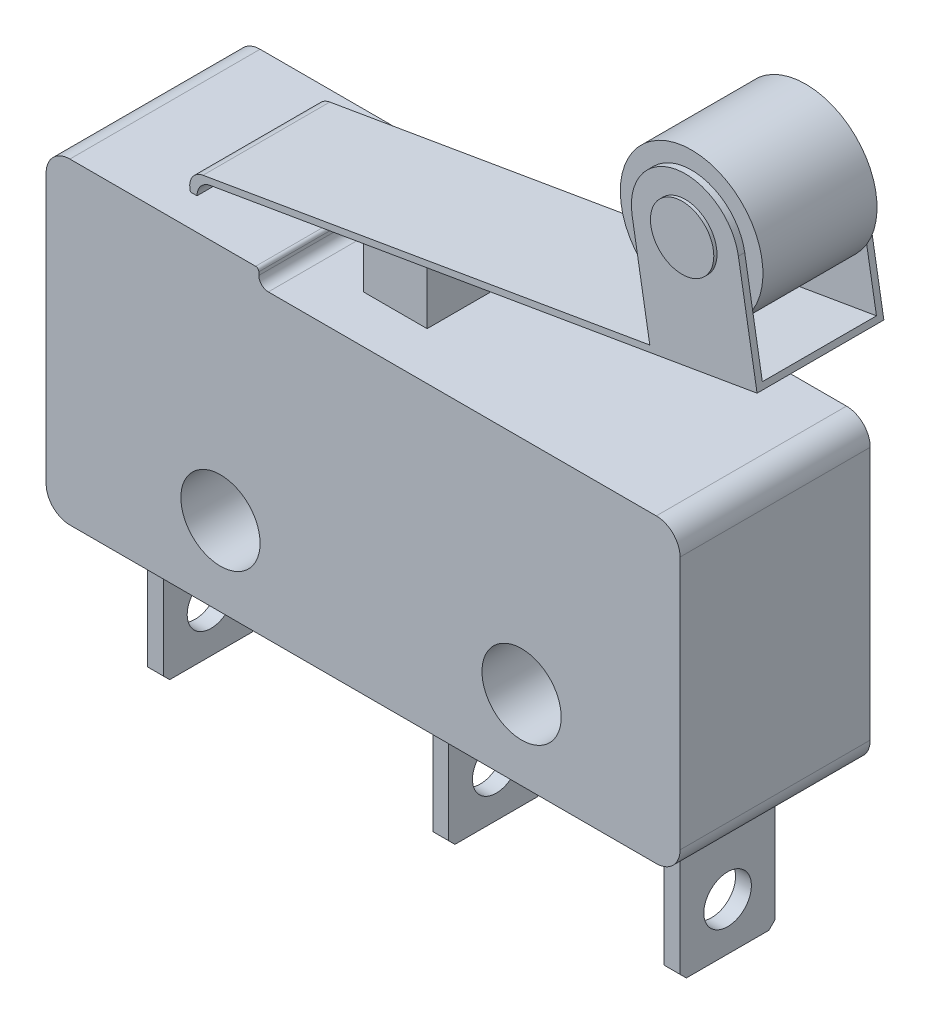
SolidWorks part; units mm, degrees
ref_plane "Alzado" through (0, 0, 0) normal (0, 0, 1) x (1, 0, 0)
ref_plane "Planta" through (0, 0, 0) normal (0, 1, 0) x (1, 0, 0)
ref_plane "Vista lateral" through (0, 0, 0) normal (1, 0, 0) x (0, 0, -1)
sketch "Croquis1" plane through (0, 0, 0) normal (0, 0, 1) x (1, 0, 0)
  line L0 (-9.25, 5) -> (-3.39, 5)
  line L1 (9.25, -5) -> (-9.25, -5)
  line L2 (10, -5) -> (10, 5) construction
  line L3 (10, 5) -> (-10, 5) construction
  line L4 (-10, -4.25) -> (-10, 4.25)
  line L5 (10, -5) -> (-10, 5) construction
  line L6 (10, 5) -> (-10, -5) construction
  line L8 (-2.99, 4.5) -> (9.25, 4.5)
  line L9 (10, 3.75) -> (10, -4.25)
  line L10 (-3.29, 4.9) -> (-3.29, 4.8)
  arc A0 (9.25, 4.5) -> (10, 3.75) centre (9.25, 3.75) cw
  arc A1 (9.25, -5) -> (10, -4.25) centre (9.25, -4.25) ccw
  arc A2 (-9.25, -5) -> (-10, -4.25) centre (-9.25, -4.25) cw
  arc A3 (-9.25, 5) -> (-10, 4.25) centre (-9.25, 4.25) ccw
  arc A4 (-3.39, 5) -> (-3.29, 4.9) centre (-3.39, 4.9) cw
  arc A5 (-3.29, 4.8) -> (-2.99, 4.5) centre (-2.99, 4.8) ccw
  circle A6 centre (-4.5, -2.5) radius 1.25
  circle A7 centre (5, -2.5) radius 1.25
  point P0 (0, 0)
  point P12 (10, 4.5)
  point P23 (-3.29, 5)
  point P26 (-3.29, 4.5)
  dimension "D5" = 0.75
  dimension "D7" = 0.1
  dimension "D8" = 0.3
  dimension "D9" = 2.5
  dimension "D11" = 5.5
  dimension "D12" = 5
  dimension "D13" = 2.5
  dimension "D1" = 10
  dimension "D2" = 9.5
  dimension "D3" = 20
  dimension "D4" = 6.71
  dimension "D6" = 13.29
  dimension "D10" = 9.5
extrude "Saliente-Extruir3" add sketch "Croquis1" along normal mid plane 6
sketch "Croquis7" plane through (0, 0, 0) normal (0, 0, 1) x (1, 0, 0)
  line L0 (-9.25, -5) -> (9.25, -5) construction
  line L1 (-7.8, -5) -> (-8.3, -5)
  line L2 (-7.8, -5) -> (-7.8, -9.35)
  line L3 (-7.8, -9.35) -> (-8.3, -9.35)
  line L4 (-8.3, -5) -> (-8.3, -9.35)
  line L5 (-7.8, -5) -> (-8.3, -9.35) construction
  line L6 (-7.8, -9.35) -> (-8.3, -5) construction
  line L8 (0.7, -5) -> (1.2, -5)
  line L9 (0.7, -5) -> (0.7, -9.35)
  line L10 (0.7, -9.35) -> (1.2, -9.35)
  line L11 (1.2, -5) -> (1.2, -9.35)
  line L12 (0.7, -5) -> (1.2, -9.35) construction
  line L13 (0.7, -9.35) -> (1.2, -5) construction
  line L14 (8, -5) -> (8.5, -5)
  line L15 (8, -5) -> (8, -9.35)
  line L16 (8, -9.35) -> (8.5, -9.35)
  line L17 (8.5, -5) -> (8.5, -9.35)
  line L18 (8, -5) -> (8.5, -9.35) construction
  line L19 (8, -9.35) -> (8.5, -5) construction
  line L20 (10, -4.25) -> (10, 3.75) construction
  point P4 (-8.05, -7.175)
  point P11 (0.95, -7.175)
  point P16 (8.25, -7.175)
  dimension "D1" = 4.35
  dimension "D2" = 0.5
  dimension "D3" = 1.5
  dimension "D4" = 8.5
  dimension "D5" = 6.8
extrude "Saliente-Extruir4" add sketch "Croquis7" along normal mid plane 3
sketch "Croquis8" plane through (8.5, 0, 0) normal (1, 0, 0) x (0, 0, -1)
  line L0 (-1.5, -9.35) -> (1.5, -9.35) construction
  line L1 (0, -7.85) -> (0, -9.35) construction
  line L2 (-1.5, -9.152) -> (-1.5, -9.35)
  line L3 (-1.5, -9.35) -> (-1.5, -5) construction
  line L4 (-1.5, -9.35) -> (-1.302, -9.35)
  line L5 (-1.302, -9.35) -> (-1.5, -9.152)
  line L6 (1.302, -9.35) -> (1.5, -9.152)
  line L7 (1.5, -9.35) -> (1.302, -9.35)
  line L8 (1.5, -9.152) -> (1.5, -9.35)
  circle A0 centre (0, -7.85) radius 0.75
  dimension "D1" = 1.5
  dimension "D2" = 1.5
  dimension "D3" = 0.28
extrude "Cortar-Extruir1" cut sketch "Croquis8" against normal through all
sketch "Croquis9" plane through (0, 0, 0) normal (0, 0, 1) x (1, 0, 0)
  line L0 (9.25, 4.5) -> (-2.99, 4.5) construction
  line L1 (-1.48, 4.5) -> (0.52, 4.5)
  line L2 (-1.48, 4.5) -> (-1.48, 6.15)
  line L3 (-1.38, 6.25) -> (0.42, 6.25)
  line L4 (0.52, 4.5) -> (0.52, 6.15)
  line L5 (-1.48, 4.5) -> (0.52, 6.25) construction
  line L6 (-1.48, 6.25) -> (0.52, 4.5) construction
  line L7 (10, -4.25) -> (10, 3.75) construction
  arc A0 (0.42, 6.25) -> (0.52, 6.15) centre (0.42, 6.15) cw
  arc A1 (-1.48, 6.15) -> (-1.38, 6.25) centre (-1.38, 6.15) cw
  point P4 (-0.48, 5.375)
  dimension "D4" = 0.1
  dimension "D1" = 9.48
  dimension "D2" = 1.75
  dimension "D3" = 2
extrude "Saliente-Extruir5" add sketch "Croquis9" along normal mid plane 3
sketch "Croquis10" plane through (0, 0, 0) normal (0, 0, 1) x (1, 0, 0)
  line L0 (-6.461, 5.0691) -> (-6.45, 5)
  line L1 (-10, 4.25) -> (-10, -4.25) construction
  line L2 (-3.39, 5) -> (-9.25, 5) construction
  line L3 (-5.82, 5.4936) -> (11.4298, 8.4421)
  line L4 (11.4298, 8.4421) -> (10.8401, 11.8921)
  line L5 (7.4887, 11.3192) -> (10.8401, 11.8921) construction
  line L6 (7.4887, 11.3192) -> (8.0447, 8.0664)
  line L7 (8.0447, 8.0664) -> (-6.0508, 5.657)
  line L8 (-6.45, 5) -> (-6.24, 5)
  line L9 (-6.45, 5) -> (-6.24, 5)
  arc A0 (-6.2299, 4.9) -> (-5.82, 5.4936) centre (-5.74, 5) cw construction
  arc A1 (10.8401, 11.8921) -> (7.4887, 11.3192) centre (9.1644, 11.6057) ccw
  circle A2 centre (9.1644, 11.6057) radius 0.5
  arc A3 (-6.0508, 5.657) -> (-6.461, 5.0691) centre (-5.97, 5.1636) ccw
  arc A4 (-6.24, 5) -> (-5.82, 5.4936) centre (-5.74, 5) cw
  dimension "D1" = 4.26
  dimension "D4" = 0.5
  dimension "D7" = 1.7
  dimension "D10" = 1
  dimension "D12" = 0.21
  dimension "D2" = 0.08
  dimension "D3" = 0.1
  dimension "D5" = 17.5
  dimension "D6" = 9.7
  dimension "D8" = 3.3
  dimension "D9" = 0.2
  dimension "D11" = 14.3
  dimension "D13" = 0.07
  dimension "D14" = 0.48
extrude "Saliente-Extruir6" add sketch "Croquis10" along normal mid plane 4 contours L8 A4 L3 L4 A1 L6 L7 A3 L0 A2
sketch "Croquis11" plane through (12.5074, 2.1379, 0) normal (0.9857, 0.1685, 0) x (0, 0, -1)
  line L1 (-1.8, 6.5956) -> (1.8, 6.5956)
  line L2 (-1.8, 6.5956) -> (-1.8, 12.0956)
  line L3 (-1.8, 12.0956) -> (1.8, 12.0956)
  line L4 (1.8, 6.5956) -> (1.8, 12.0956)
  line L5 (-1.8, 6.5956) -> (1.8, 12.0956) construction
  line L6 (-1.8, 12.0956) -> (1.8, 6.5956) construction
  line L7 (0, 9.3456) -> (0, 9.8956) construction
  line L8 (-2, 9.8956) -> (2, 9.8956) construction
  line L9 (-2, 6.3956) -> (2, 6.3956) construction
  point P4 (0, 9.3456)
  dimension "D1" = 3.6
  dimension "D2" = 5.5
  dimension "D3" = 0.2
extrude "Cortar-Extruir2" cut sketch "Croquis11" against normal up to next
sketch "Croquis12" plane through (0, 0, 1.8) normal (0, 0, -1) x (-1, 0, 0)
  circle A1 centre (-9.1644, 11.6057) radius 2.25
  dimension "D1" = 4.5
extrude "Saliente-Extruir8" add sketch "Croquis12" along normal up to surface (3.6 mm away) up to face at (8.6644, 11.6057, -1.8)
sketch "Croquis13" plane through (0, 0, 0) normal (0, 0, 1) x (1, 0, 0)
  circle A0 centre (9.1644, 11.6057) radius 1
  dimension "D1" = 2
extrude "Saliente-Extruir9" add sketch "Croquis13" along normal mid plane 4.2
